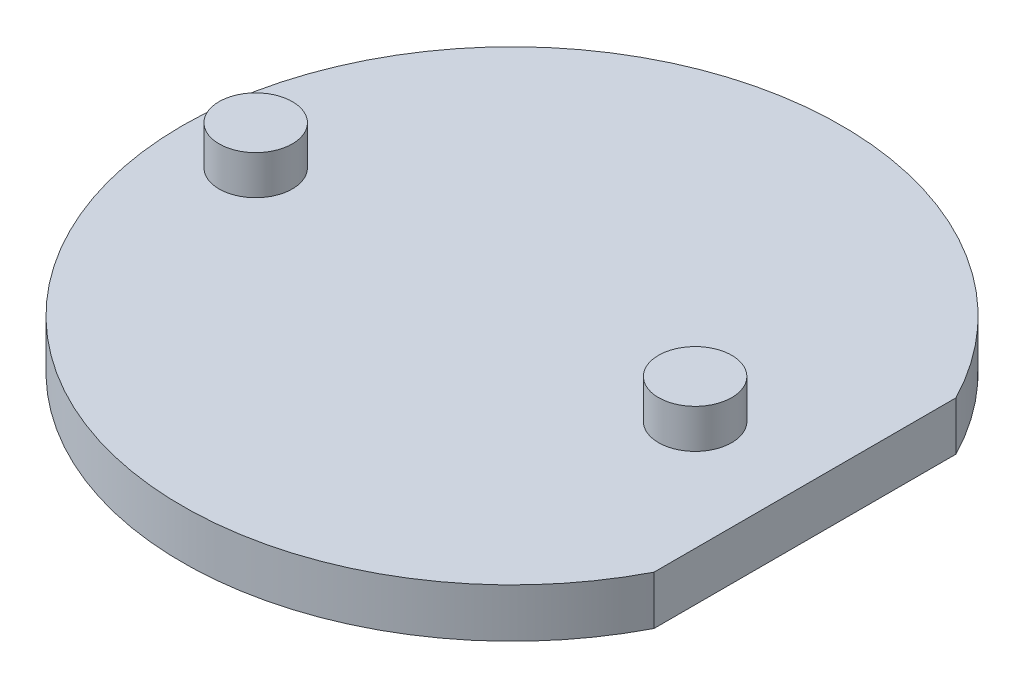
SolidWorks part; units mm, degrees
ref_plane "Alzado" through (0, 0, 0) normal (0, 0, 1) x (1, 0, 0)
ref_plane "Planta" through (0, 0, 0) normal (0, 1, 0) x (1, 0, 0)
ref_plane "Vista lateral" through (0, 0, 0) normal (1, 0, 0) x (0, 0, -1)
sketch "Croquis2" plane through (0, 0, 0) normal (0, 1, 0) x (1, 0, 0)
  line L0 (12, 6.1847) -> (12, -6.1847)
  arc A0 (12, 6.1847) -> (12, -6.1847) centre (0, 0) ccw
  arc A1 (12, -6.1847) -> (12, 6.1847) centre (0, 0) ccw construction
  dimension "D2" = 27
  dimension "D1" = 1.5
extrude "Saliente-Extruir1" add sketch "Croquis2" along normal blind 2
sketch "Croquis3" plane through (0, 2, 0) normal (0, 1, 0) x (1, 0, 0)
  line L0 (-1000, 0) -> (49000, 0) construction
  circle A1 centre (-10.5, 0) radius 1.5
  circle A2 centre (7.5, 0) radius 1.5
  arc A3 (12, 6.1847) -> (12, -6.1847) centre (0, 0) ccw construction
  dimension "D1" = 3
  dimension "D2" = 21
  dimension "D3" = 1.5
extrude "Saliente-Extruir2" add sketch "Croquis3" along normal blind 1.6
sketch "Croquis4" plane through (0, 0, 0) normal (0, -1, 0) x (1, 0, 0)
  circle A0 centre (0, 0) radius 2.5
  dimension "D2" = 5
extrude "Saliente-Extruir3" add sketch "Croquis4" along normal blind 2
